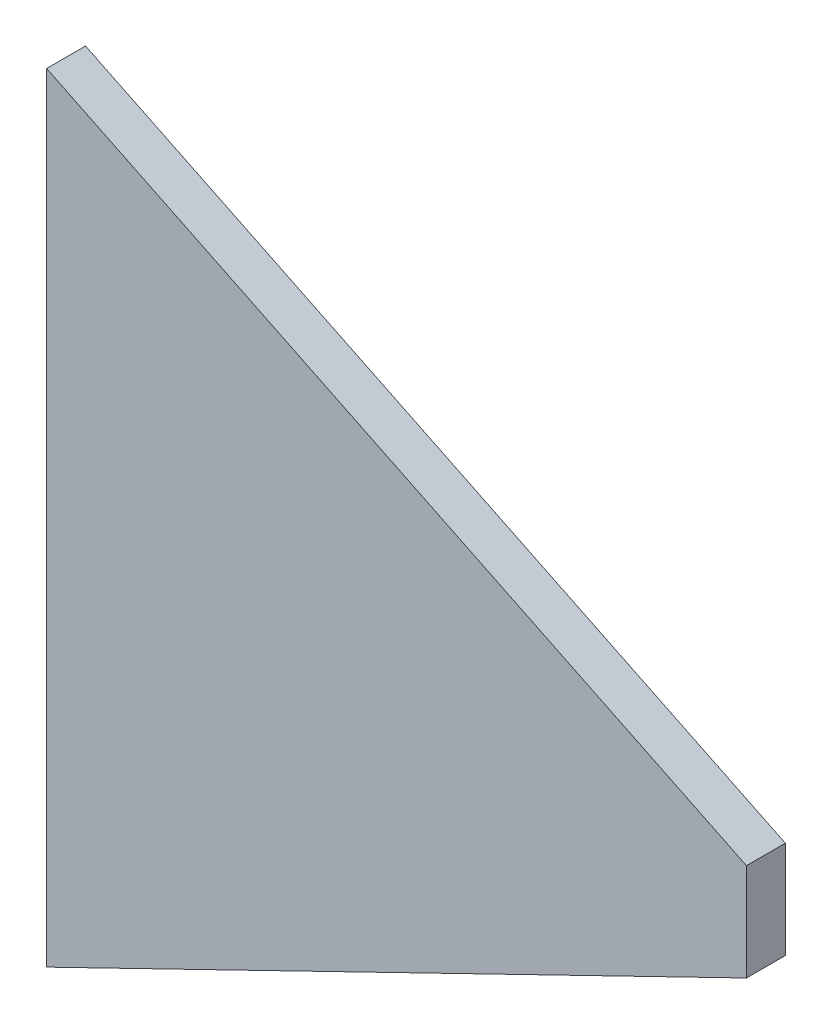
SolidWorks part; units mm, degrees
ref_plane "Front Plane" through (0, 0, 0) normal (0, 0, 1) x (1, 0, 0)
ref_plane "Top Plane" through (0, 0, 0) normal (0, 1, 0) x (1, 0, 0)
ref_plane "Right Plane" through (0, 0, 0) normal (1, 0, 0) x (0, 0, -1)
sketch "Sketch1" plane through (0, 0, 0) normal (0, 0, 1) x (1, 0, 0)
  line L0 (0, 0) -> (0, 3.175)
  line L1 (0, 3.175) -> (-22.8401, 14.2875)
  line L2 (-22.8401, 14.2875) -> (-22.8401, -11.1125)
  line L3 (-22.8401, -11.1125) -> (0, 0)
  dimension "D1" = 25.4
  dimension "D2" = 25.4
  dimension "D3" = 3.175
  dimension "D4" = 25.4
extrude "Boss-Extrude1" add sketch "Sketch1" along normal blind 1.27
sketch "Sketch2" plane through (0, 0, 1.27) normal (0, 0, 1) x (1, 0, 0)
  line L0 (0, 1.5875) -> (-2.54, 1.5875) construction
  line L1 (0, 0) -> (0, 3.175) construction
  dimension "D1" = 2.54
